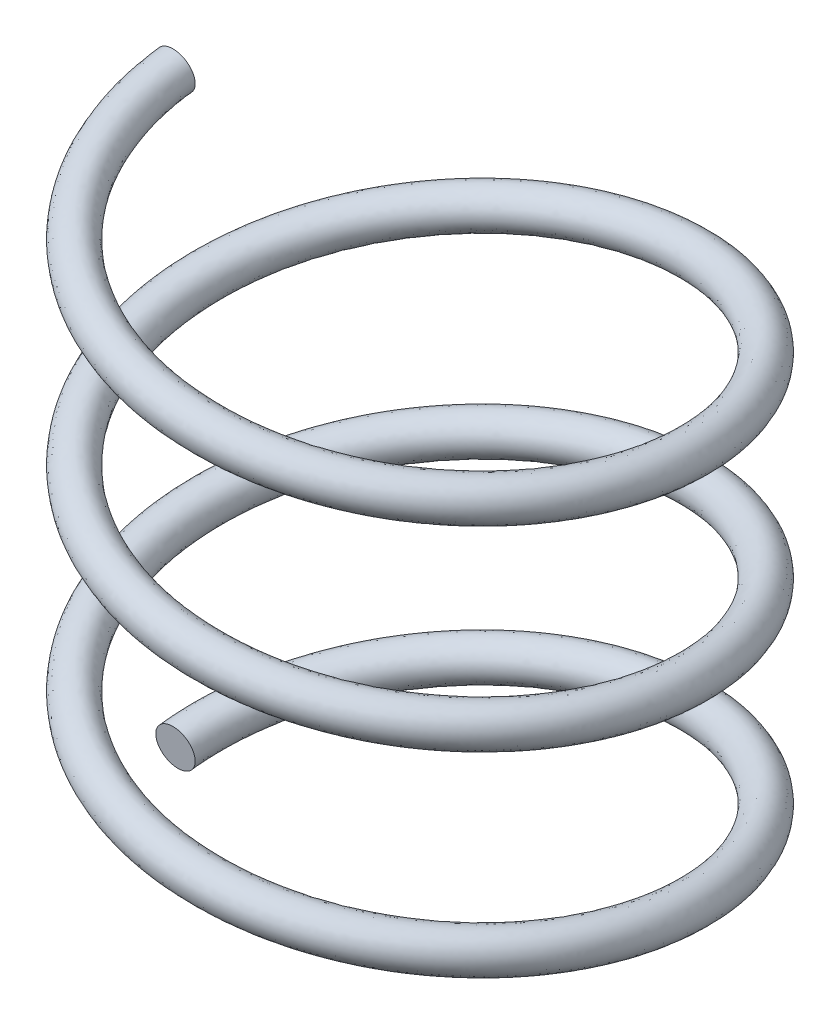
SolidWorks part; units mm, degrees
ref_plane "Front Plane" through (0, 0, 0) normal (0, 0, 1) x (1, 0, 0)
ref_plane "Top Plane" through (0, 0, 0) normal (0, 1, 0) x (1, 0, 0)
ref_plane "Right Plane" through (0, 0, 0) normal (1, 0, 0) x (0, 0, -1)
sketch "Sketch11" plane through (0, 0, 0) normal (0, 1, 0) x (1, 0, 0)
  circle A0 centre (-0.7292, 3.1818) radius 12.5
  dimension "D1" = 25
curve "Helix/Spiral1" pitch 10 height 30 turns 3
ref_plane "Plane1" through (-13.2292, 0, -3.1818) normal (0, 0.1263, -0.992) x (-1, 0, 0)
sketch "Sketch19" plane through (-13.2292, 0, -3.1818) normal (0, 0.1263, -0.992) x (-1, 0, 0)
  circle A0 centre (0, 0) radius 1
  ellipse E0 centre (-12.5, 0) end of major axis (0, 0) minor radius 1.5788 construction
sweep "Sweep4" add profiles "Sketch19" path "Helix/Spiral1"
